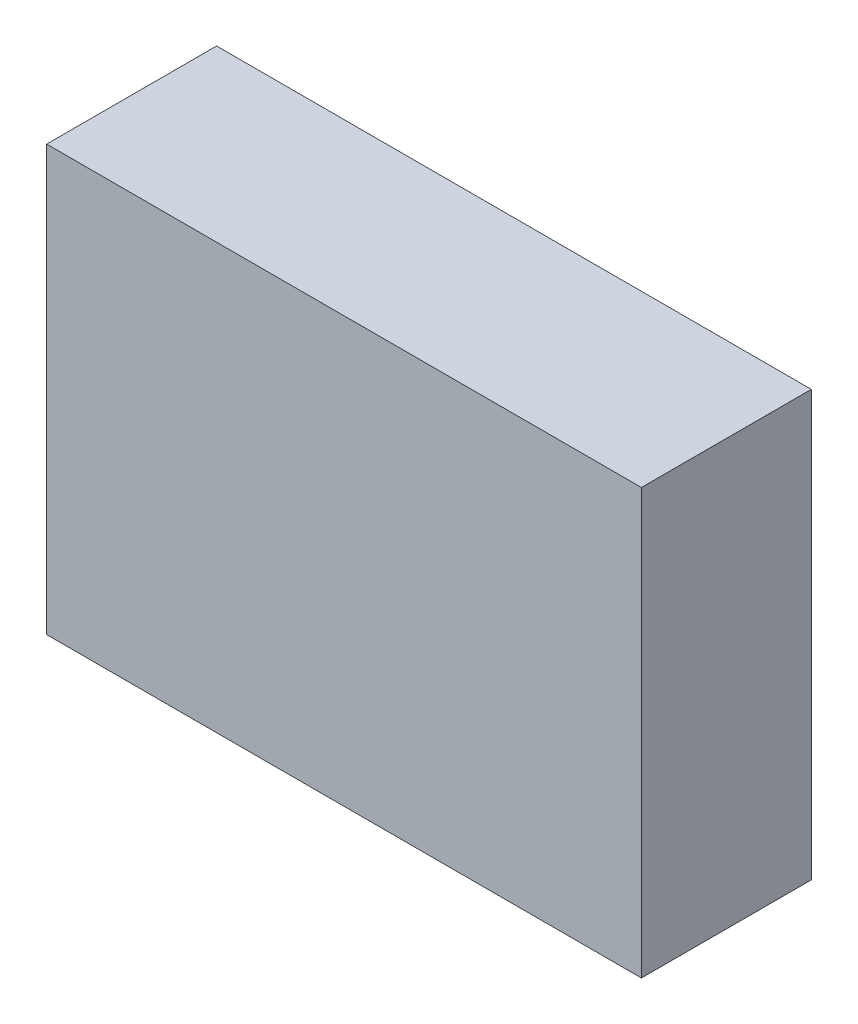
SolidWorks part; units mm, degrees
ref_plane "Front Plane" through (0, 0, 0) normal (0, 0, 1) x (1, 0, 0)
ref_plane "Top Plane" through (0, 0, 0) normal (0, 1, 0) x (1, 0, 0)
ref_plane "Right Plane" through (0, 0, 0) normal (1, 0, 0) x (0, 0, -1)
sketch "Sketch2" plane through (0, 0, 0) normal (0, 0, 1) x (1, 0, 0)
  line L0 (0, -999.2625) -> (0, 49000.7375) construction
  line L1 (-3.5, 2.8509) -> (3.5, 2.8509)
  line L2 (-3.5, 2.8509) -> (-3.5, -2.1491)
  line L3 (-3.5, -2.1491) -> (3.5, -2.1491)
  line L4 (3.5, 2.8509) -> (3.5, -2.1491)
  line L5 (0, -55) -> (0, 55) construction
  dimension "D1" = 5
  dimension "D2" = 7
  dimension "D3" = 3.5
  dimension "D4" = 0
extrude "Boss-Extrude1" add sketch "Sketch2" along normal blind 2
sketch "Sketch3" plane through (0, -2.1491, 0) normal (0, -1, 0) x (1, 0, 0)
  line L0 (2.75, 0) -> (-2.75, 0) construction
  line L1 (-3.25, 1.75) -> (3.25, 1.75)
  line L2 (-3.25, 1.75) -> (-3.25, 0.25)
  line L3 (-3.25, 0.25) -> (3.25, 0.25)
  line L4 (3.25, 1.75) -> (3.25, 0.25)
  line L5 (-3.5, 2) -> (3.5, 2) construction
  line L6 (-3.5, 2) -> (-3.5, 0) construction
  line L7 (3.5, 2) -> (3.5, 0) construction
  dimension "D1" = 0.25
  dimension "D2" = 0.25
  dimension "D3" = 0.25
  dimension "D4" = 0.25
extrude "Cut-Extrude1" cut sketch "Sketch3" against normal blind 0.5
sketch "Sketch5" plane through (3.5, 0, 0) normal (1, 0, 0) x (0, 0, -1)
  line L1 (-1.8873, 2.7146) -> (-0.1235, 2.7146)
  line L2 (-1.8873, 2.7146) -> (-1.8873, -1.9852)
  line L3 (-1.8873, -1.9852) -> (-0.1235, -1.9852)
  line L4 (-0.1235, 2.7146) -> (-0.1235, -1.9852)
